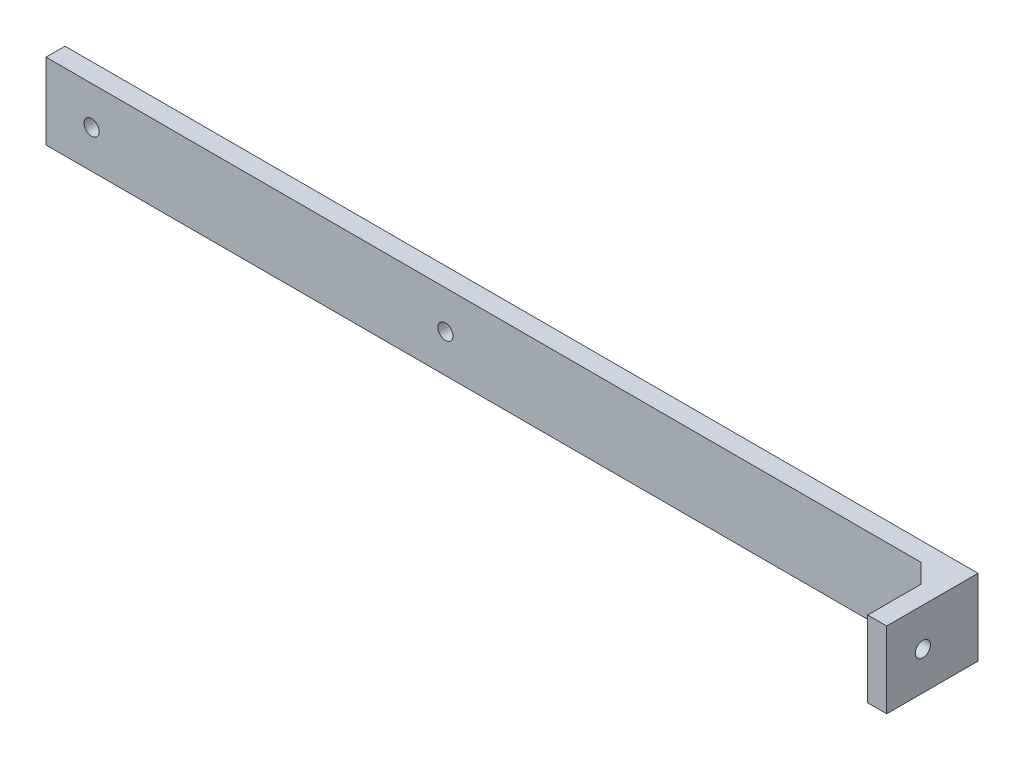
SolidWorks part; units mm, degrees
ref_plane "Front Plane" through (0, 0, 0) normal (0, 0, 1) x (1, 0, 0)
ref_plane "Top Plane" through (0, 0, 0) normal (0, 1, 0) x (1, 0, 0)
ref_plane "Right Plane" through (0, 0, 0) normal (1, 0, 0) x (0, 0, -1)
sketch "Sketch1" plane through (0, 0, 0) normal (0, 0, 1) x (1, 0, 0)
  line L1 (-120, -10) -> (120, -10)
  line L2 (-120, -10) -> (-120, 10)
  line L3 (-120, 10) -> (120, 10)
  line L4 (120, -10) -> (120, 10)
  line L5 (-120, -10) -> (120, 10) construction
  line L6 (-120, 10) -> (120, -10) construction
  point P0 (0, 0)
  dimension "D1" = 20
  dimension "D2" = 240
extrude "Boss-Extrude1" add sketch "Sketch1" along normal blind 5
sketch "Sketch2" plane through (0, 0, 5) normal (0, 0, 1) x (1, 0, 0)
  line L0 (-120, -10) -> (120, -10) construction
  line L1 (120, 10) -> (115, 10)
  line L2 (120, 10) -> (120, -10)
  line L3 (120, -10) -> (115, -10)
  line L4 (115, 10) -> (115, -10)
  dimension "D1" = 5
extrude "Boss-Extrude2" add sketch "Sketch2" along normal blind 19
sketch "Sketch3" plane through (120, 0, 0) normal (1, 0, 0) x (0, 0, -1)
  line L0 (-24, -10) -> (0, -10) construction
  line L1 (-24, -10) -> (-24, 10) construction
  circle A0 centre (-14.5, 0) radius 2
  dimension "D1" = 4
  dimension "D2" = 10
  dimension "D3" = 9.5
extrude "Cut-Extrude1" cut sketch "Sketch3" against normal through all
sketch "Sketch4" plane through (115, 0, 0) normal (-1, 0, 0) x (0, 0, 1)
  line L1 (5, -10) -> (10, -10)
  line L2 (5, -10) -> (5, -5)
  line L3 (5, -5) -> (10, -5)
  line L4 (10, -10) -> (10, -5)
  line L5 (5, 10) -> (10, 10)
  line L6 (5, 10) -> (5, 5)
  line L7 (5, 5) -> (10, 5)
  line L8 (10, 10) -> (10, 5)
  dimension "D1" = 5
  dimension "D2" = 5
  dimension "D3" = 5
  dimension "D4" = 5
extrude "Boss-Extrude3" add sketch "Sketch4" along normal blind 5
sketch "Sketch5" plane through (0, -10, 0) normal (0, -1, 0) x (1, 0, 0)
  line L0 (110, 5) -> (115, 10)
  line L1 (115, 10) -> (110, 10)
  line L2 (110, 10) -> (110, 5)
extrude "Cut-Extrude2" cut sketch "Sketch5" against normal through all
sketch "Sketch6" plane through (0, 0, 0) normal (0, 0, -1) x (-1, 0, 0)
  line L0 (-120, -10) -> (-120, 10) construction
  line L1 (120, -10) -> (-120, -10) construction
  circle A0 centre (108, 0) radius 2
  dimension "D1" = 4
  dimension "D2" = 228
  dimension "D3" = 10
extrude "Cut-Extrude3" cut sketch "Sketch6" against normal through all
sketch "Sketch7" plane through (0, 0, 0) normal (0, 0, -1) x (-1, 0, 0)
  line L0 (-120, -10) -> (-120, 10) construction
  circle A0 centre (15, 0) radius 2
  dimension "D1" = 4
  dimension "D2" = 135
extrude "Cut-Extrude4" cut sketch "Sketch7" against normal blind 10
